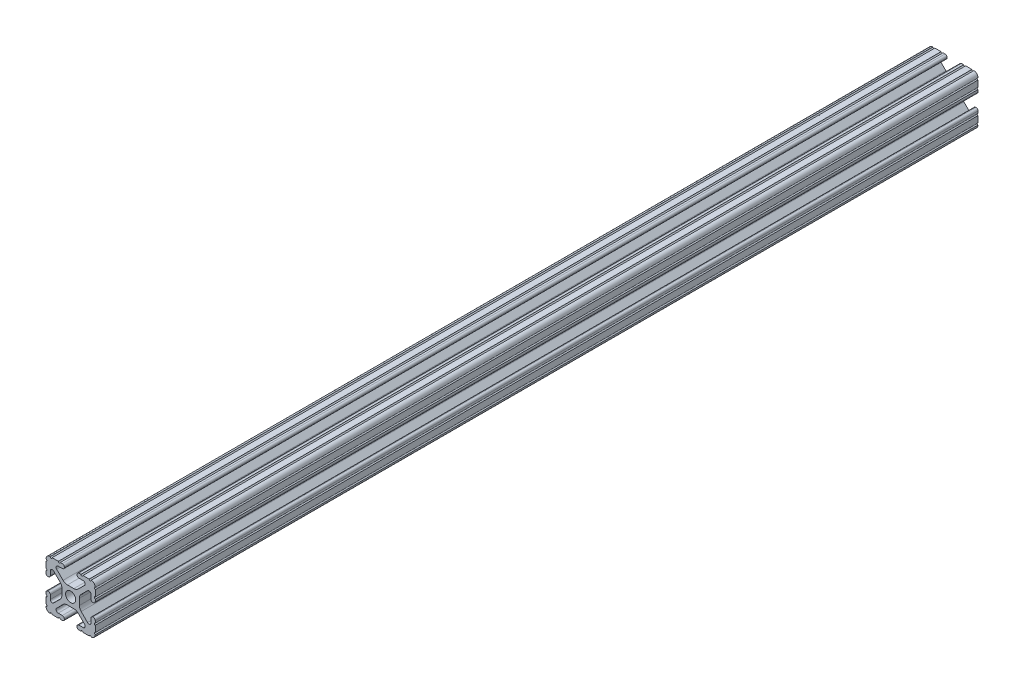
SolidWorks part; units mm, degrees
material "6061 Alloy"
ref_plane "Front Plane" through (0, 0, 0) normal (0, 0, 1) x (1, 0, 0)
ref_plane "Top Plane" through (0, 0, 0) normal (0, 1, 0) x (1, 0, 0)
ref_plane "Right Plane" through (0, 0, 0) normal (1, 0, 0) x (0, 0, -1)
sketch "Sketch1" plane through (0, 0, 0) normal (0, 0, 1) x (1, 0, 0)
  line L88 (-7.1797, -8.6452) -> (-3.9523, -5.4237)
  line L89 (-1.7093, -4.4958) -> (1.7093, -4.4958)
  line L90 (3.9523, -5.4237) -> (7.1797, -8.6452)
  line L91 (6.4164, -10.4902) -> (4.2875, -10.4902)
  line L92 (3.2385, -11.5392) -> (3.2385, -11.651)
  line L93 (4.2875, -12.7) -> (5.3171, -12.7)
  line L94 (6.3331, -12.7) -> (9.5504, -12.7)
  line L95 (12.7, -9.5504) -> (12.7, -6.3331)
  line L96 (12.7, -5.3171) -> (12.7, -4.2875)
  line L97 (11.651, -3.2385) -> (11.5392, -3.2385)
  line L98 (10.4902, -4.2875) -> (10.4902, -6.4021)
  line L99 (8.7371, -7.1294) -> (5.441, -3.8408)
  line L100 (4.5085, -1.5932) -> (4.5085, 1.5932)
  line L101 (5.441, 3.8408) -> (8.7371, 7.1294)
  line L102 (10.4902, 6.4021) -> (10.4902, 4.2875)
  line L103 (11.5392, 3.2385) -> (11.651, 3.2385)
  line L104 (12.7, 4.2875) -> (12.7, 5.3171)
  line L105 (12.7, 6.3331) -> (12.7, 9.5504)
  line L106 (9.5504, 12.7) -> (6.3331, 12.7)
  line L107 (5.3171, 12.7) -> (4.2875, 12.7)
  line L108 (3.2385, 11.651) -> (3.2385, 11.5392)
  line L109 (4.2875, 10.4902) -> (6.4768, 10.4902)
  line L110 (7.207, 8.7244) -> (3.8983, 5.4232)
  line L111 (1.6558, 4.4958) -> (-1.6558, 4.4958)
  line L112 (-3.8983, 5.4232) -> (-7.207, 8.7244)
  line L113 (-6.4768, 10.4902) -> (-4.2875, 10.4902)
  line L114 (-3.2385, 11.5392) -> (-3.2385, 11.651)
  line L115 (-4.2875, 12.7) -> (-5.3171, 12.7)
  line L116 (-6.3331, 12.7) -> (-9.5504, 12.7)
  line L117 (-12.7, 9.5504) -> (-12.7, 6.3331)
  line L118 (-12.7, 5.3171) -> (-12.7, 4.2875)
  line L119 (-11.651, 3.2385) -> (-11.5392, 3.2385)
  line L120 (-10.4902, 4.2875) -> (-10.4902, 6.4021)
  line L121 (-8.7371, 7.1294) -> (-5.441, 3.8408)
  line L122 (-4.5085, 1.5932) -> (-4.5085, -1.5932)
  line L123 (-5.441, -3.8408) -> (-8.7371, -7.1294)
  line L124 (-10.4902, -6.4021) -> (-10.4902, -4.2875)
  line L125 (-11.5392, -3.2385) -> (-11.651, -3.2385)
  line L126 (-12.7, -4.2875) -> (-12.7, -5.3171)
  line L127 (-12.7, -6.3331) -> (-12.7, -9.5504)
  line L128 (-9.5504, -12.7) -> (-6.3331, -12.7)
  line L129 (-5.3171, -12.7) -> (-4.2875, -12.7)
  line L130 (-3.2385, -11.651) -> (-3.2385, -11.5392)
  line L131 (-4.2875, -10.4902) -> (-6.4164, -10.4902)
  circle A1 centre (0, 0) radius 2.6035
  arc A104 (-7.1797, -8.6452) -> (-6.4164, -10.4902) centre (-6.4164, -9.4098) ccw
  arc A105 (-1.7093, -4.4958) -> (-3.9523, -5.4237) centre (-1.7093, -7.6708) ccw
  arc A106 (3.9523, -5.4237) -> (1.7093, -4.4958) centre (1.7093, -7.6708) ccw
  arc A107 (6.4164, -10.4902) -> (7.1797, -8.6452) centre (6.4164, -9.4098) ccw
  arc A108 (4.2875, -10.4902) -> (3.2385, -11.5392) centre (4.2875, -11.5392) ccw
  arc A109 (3.2385, -11.651) -> (4.2875, -12.7) centre (4.2875, -11.651) ccw
  arc A110 (6.3331, -12.7) -> (5.3171, -12.7) centre (5.8251, -12.7) ccw
  arc A111 (10.5664, -12.6998) -> (9.5504, -12.7) centre (10.0584, -12.7) ccw
  arc A112 (10.5664, -12.6998) -> (12.6998, -10.5664) centre (10.5918, -10.5918) ccw
  arc A113 (12.7, -9.5504) -> (12.6998, -10.5664) centre (12.7, -10.0584) ccw
  arc A114 (12.7, -5.3171) -> (12.7, -6.3331) centre (12.7, -5.8251) ccw
  arc A115 (12.7, -4.2875) -> (11.651, -3.2385) centre (11.651, -4.2875) ccw
  arc A116 (11.5392, -3.2385) -> (10.4902, -4.2875) centre (11.5392, -4.2875) ccw
  arc A117 (8.7371, -7.1294) -> (10.4902, -6.4021) centre (9.4628, -6.4021) ccw
  arc A118 (4.5085, -1.5932) -> (5.441, -3.8408) centre (7.6835, -1.5932) ccw
  arc A119 (5.441, 3.8408) -> (4.5085, 1.5932) centre (7.6835, 1.5932) ccw
  arc A120 (10.4902, 6.4021) -> (8.7371, 7.1294) centre (9.4628, 6.4021) ccw
  arc A121 (10.4902, 4.2875) -> (11.5392, 3.2385) centre (11.5392, 4.2875) ccw
  arc A122 (11.651, 3.2385) -> (12.7, 4.2875) centre (11.651, 4.2875) ccw
  arc A123 (12.7, 6.3331) -> (12.7, 5.3171) centre (12.7, 5.8251) ccw
  arc A124 (12.6998, 10.5664) -> (12.7, 9.5504) centre (12.7, 10.0584) ccw
  arc A125 (12.6998, 10.5664) -> (10.5664, 12.6998) centre (10.5918, 10.5918) ccw
  arc A126 (9.5504, 12.7) -> (10.5664, 12.6998) centre (10.0584, 12.7) ccw
  arc A127 (5.3171, 12.7) -> (6.3331, 12.7) centre (5.8251, 12.7) ccw
  arc A128 (4.2875, 12.7) -> (3.2385, 11.651) centre (4.2875, 11.651) ccw
  arc A129 (3.2385, 11.5392) -> (4.2875, 10.4902) centre (4.2875, 11.5392) ccw
  arc A130 (7.207, 8.7244) -> (6.4768, 10.4902) centre (6.4768, 9.4563) ccw
  arc A131 (1.6558, 4.4958) -> (3.8983, 5.4232) centre (1.6558, 7.6708) ccw
  arc A132 (-3.8983, 5.4232) -> (-1.6558, 4.4958) centre (-1.6558, 7.6708) ccw
  arc A133 (-6.4768, 10.4902) -> (-7.207, 8.7244) centre (-6.4768, 9.4563) ccw
  arc A134 (-4.2875, 10.4902) -> (-3.2385, 11.5392) centre (-4.2875, 11.5392) ccw
  arc A135 (-3.2385, 11.651) -> (-4.2875, 12.7) centre (-4.2875, 11.651) ccw
  arc A136 (-6.3331, 12.7) -> (-5.3171, 12.7) centre (-5.8251, 12.7) ccw
  arc A137 (-10.5664, 12.6998) -> (-9.5504, 12.7) centre (-10.0584, 12.7) ccw
  arc A138 (-10.5664, 12.6998) -> (-12.6998, 10.5664) centre (-10.5918, 10.5918) ccw
  arc A139 (-12.7, 9.5504) -> (-12.6998, 10.5664) centre (-12.7, 10.0584) ccw
  arc A140 (-12.7, 5.3171) -> (-12.7, 6.3331) centre (-12.7, 5.8251) ccw
  arc A141 (-12.7, 4.2875) -> (-11.651, 3.2385) centre (-11.651, 4.2875) ccw
  arc A142 (-11.5392, 3.2385) -> (-10.4902, 4.2875) centre (-11.5392, 4.2875) ccw
  arc A143 (-8.7371, 7.1294) -> (-10.4902, 6.4021) centre (-9.4628, 6.4021) ccw
  arc A144 (-4.5085, 1.5932) -> (-5.441, 3.8408) centre (-7.6835, 1.5932) ccw
  arc A145 (-5.441, -3.8408) -> (-4.5085, -1.5932) centre (-7.6835, -1.5932) ccw
  arc A146 (-10.4902, -6.4021) -> (-8.7371, -7.1294) centre (-9.4628, -6.4021) ccw
  arc A147 (-10.4902, -4.2875) -> (-11.5392, -3.2385) centre (-11.5392, -4.2875) ccw
  arc A148 (-11.651, -3.2385) -> (-12.7, -4.2875) centre (-11.651, -4.2875) ccw
  arc A149 (-12.7, -6.3331) -> (-12.7, -5.3171) centre (-12.7, -5.8251) ccw
  arc A150 (-12.6998, -10.5664) -> (-12.7, -9.5504) centre (-12.7, -10.0584) ccw
  arc A151 (-12.6998, -10.5664) -> (-10.5664, -12.6998) centre (-10.5918, -10.5918) ccw
  arc A152 (-9.5504, -12.7) -> (-10.5664, -12.6998) centre (-10.0584, -12.7) ccw
  arc A153 (-5.3171, -12.7) -> (-6.3331, -12.7) centre (-5.8251, -12.7) ccw
  arc A154 (-4.2875, -12.7) -> (-3.2385, -11.651) centre (-4.2875, -11.651) ccw
  arc A155 (-3.2385, -11.5392) -> (-4.2875, -10.4902) centre (-4.2875, -11.5392) ccw
extrude "Boss-Extrude1" add sketch "Sketch1" along normal mid plane 455.168
